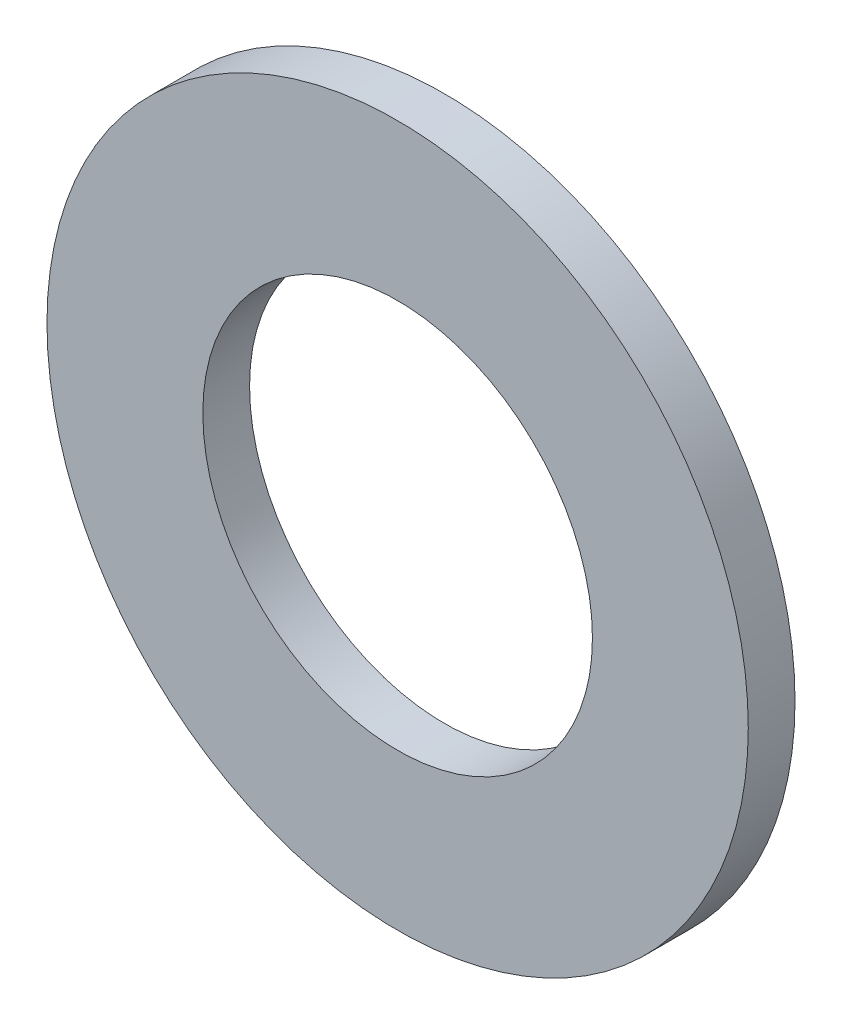
SolidWorks part; units mm, degrees
ref_plane "Front Plane" through (0, 0, 0) normal (0, 0, 1) x (1, 0, 0)
ref_plane "Top Plane" through (0, 0, 0) normal (0, 1, 0) x (1, 0, 0)
ref_plane "Right Plane" through (0, 0, 0) normal (1, 0, 0) x (0, 0, -1)
sketch "Sketch1" plane through (0, 0, 0) normal (0, 0, 1) x (1, 0, 0)
  circle A0 centre (0, 0) radius 22.5
  dimension "D1" = 45
extrude "Boss-Extrude1" add sketch "Sketch1" along normal blind 3
sketch "Sketch2" plane through (0, 0, 3) normal (0, 0, 1) x (1, 0, 0)
  circle A0 centre (0, 0) radius 12.5
  dimension "D1" = 25
extrude "Cut-Extrude1" cut sketch "Sketch2" against normal blind 3
